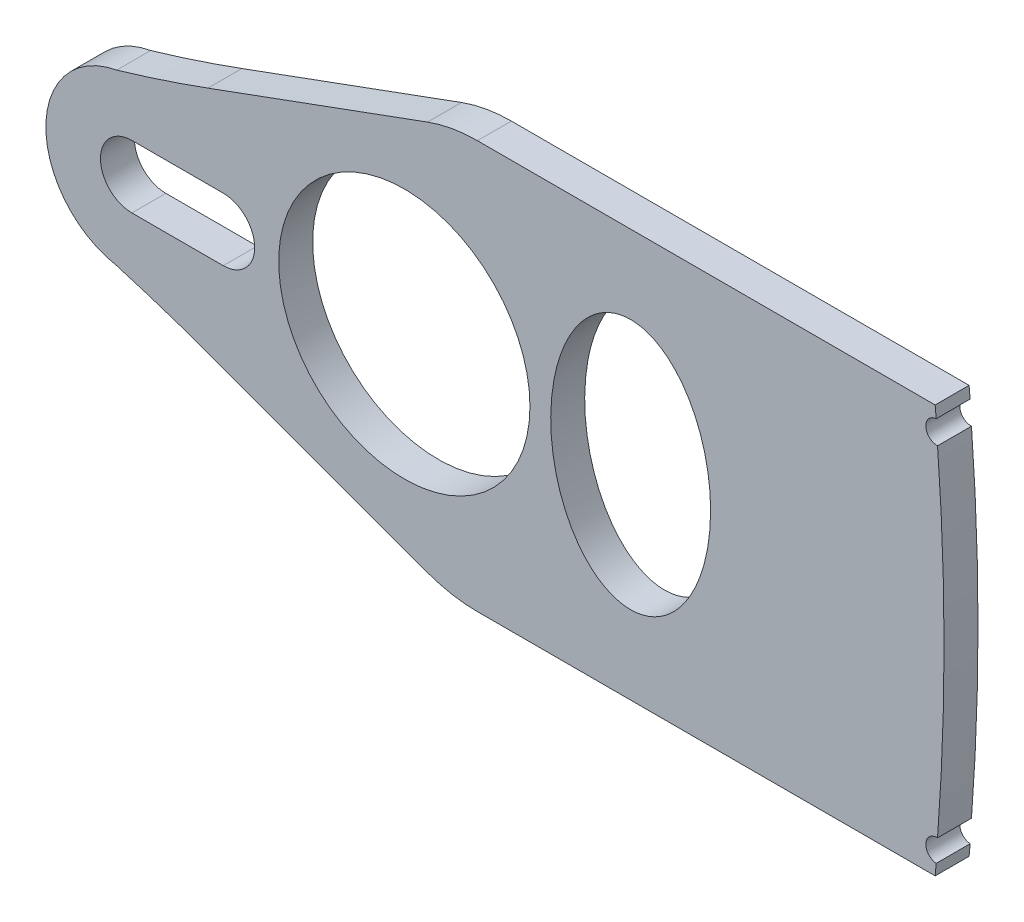
SolidWorks part; units mm, degrees
ref_plane "Front Plane" through (0, 0, 0) normal (0, 0, 1) x (1, 0, 0)
ref_plane "Top Plane" through (0, 0, 0) normal (0, 1, 0) x (1, 0, 0)
ref_plane "Right Plane" through (0, 0, 0) normal (1, 0, 0) x (0, 0, -1)
sketch "Sketch1" plane through (0, 0, 0) normal (0, 0, 1) x (1, 0, 0)
  line L2 (-17.8942, -7.2554) -> (1.5045, -14.3568)
  line L3 (5.9104, -15.1378) -> (28.8262, -15.1378)
  line L4 (-16.5455, 0.1069) -> (-24.6191, 0.1069)
  line L6 (-29.4127, 2.8822) -> (46.9452, 2.8822) construction
  line L7 (28.8262, 20.9022) -> (46.3587, 20.9022)
  line L9 (28.8262, -15.1378) -> (46.3587, -15.1378)
  line L10 (-16.5455, 5.6575) -> (-24.6191, 5.6575)
  line L11 (5.9104, 20.9022) -> (28.8262, 20.9022)
  line L12 (-17.8942, 13.0198) -> (1.5045, 20.1211)
  arc A8 (-25.9651, 10.3652) -> (-25.9651, -4.6008) centre (-24.6191, 2.8822) ccw
  arc A9 (-17.8942, -7.2554) -> (-25.9651, -4.6008) centre (-61.9532, -127.6116) ccw
  arc A10 (1.5045, -14.3568) -> (5.9104, -15.1378) centre (5.9104, -2.3211) ccw
  circle A12 centre (-0.5455, 2.8822) radius 11.1011
  arc A13 (-24.6191, 5.6575) -> (-24.6191, 0.1069) centre (-24.6191, 2.8822) ccw
  arc A14 (-16.5455, 0.1069) -> (-16.5455, 5.6575) centre (-16.5455, 2.8822) ccw
  arc A15 (45.5531, -12.9287) -> (46.4491, -14.1315) centre (46.5427, -13.1266) ccw
  arc A16 (46.5696, -12.1178) -> (45.5531, -12.9287) centre (46.5427, -13.1266) ccw
  arc A17 (46.5696, -12.1178) -> (46.5696, 17.8822) centre (-148.7033, 2.8822) ccw
  arc A21 (46.3587, -15.1378) -> (46.4491, -14.1315) centre (-148.7033, 2.8822) ccw
  arc A22 (46.3587, 20.9022) -> (46.4491, 19.8959) centre (-148.7033, 2.8822) cw
  arc A23 (46.5696, 17.8822) -> (45.5531, 18.6931) centre (46.5427, 18.891) cw
  arc A24 (45.5531, 18.6931) -> (46.4491, 19.8959) centre (46.5427, 18.891) cw
  arc A25 (1.5045, 20.1211) -> (5.9104, 20.9022) centre (5.9104, 8.0855) cw
  arc A26 (-17.8942, 13.0198) -> (-25.9651, 10.3652) centre (-61.9532, 133.376) cw
  ellipse E0 centre (19.4545, 2.8822) end of major axis (19.4545, -8.2189) minor radius 7.0643
  point P5 (26.5188, 2.8822)
  point P6 (12.3901, 2.8822)
  point P7 (0, 0)
  point P8 (0, 0)
  point P9 (0, 0)
  point P42 (-0.5455, 2.8822)
  point P45 (19.4545, 2.8822)
  point P46 (19.4545, 20.9022)
  point P47 (19.4545, -15.1378)
  dimension "D4" = 30
  dimension "D1" = 16
  dimension "D2" = 1.0064
  dimension "D3" = 2.0137
extrude "Boss-Extrude1" add sketch "Sketch1" along normal blind 3
